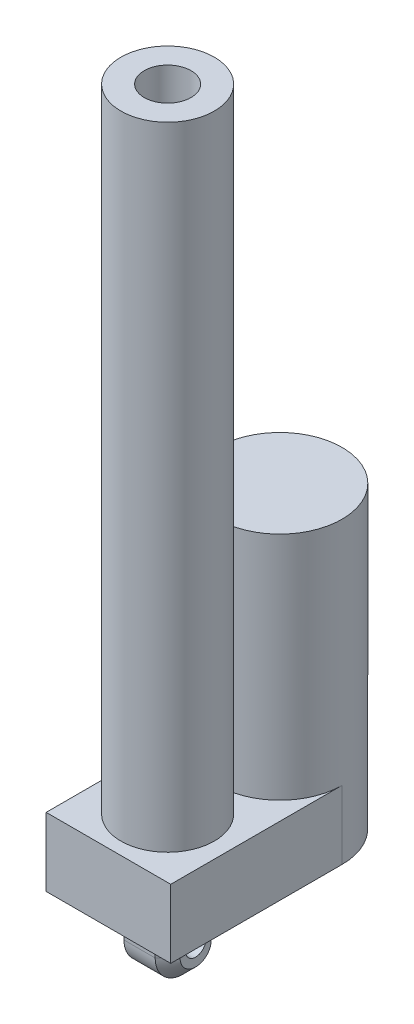
SolidWorks part; units mm, degrees
ref_plane "前视基准面" through (0, 0, 0) normal (0, 0, 1) x (1, 0, 0)
ref_plane "上视基准面" through (0, 0, 0) normal (0, 1, 0) x (1, 0, 0)
ref_plane "右视基准面" through (0, 0, 0) normal (1, 0, 0) x (0, 0, -1)
sketch "草图1" plane through (0, 0, 0) normal (0, 1, 0) x (1, 0, 0)
  line L1 (-20, -27.5) -> (20, -27.5)
  line L2 (-20, -27.5) -> (-20, 27.5)
  line L4 (20, -27.5) -> (20, 27.5)
  line L5 (-20, -27.5) -> (20, 27.5) construction
  line L6 (-20, 27.5) -> (20, -27.5) construction
  arc A0 (20, 27.5) -> (-20, 27.5) centre (0, 27.5) ccw
  point P0 (0, 0)
  dimension "D2" = 55
  dimension "D1" = 40
extrude "凸台-拉伸1" add sketch "草图1" along normal blind 22
sketch "草图2" plane through (0, 22, 0) normal (0, 1, 0) x (1, 0, 0)
  circle A0 centre (0, 27.5) radius 20
  dimension "D2" = 40
extrude "凸台-拉伸2" add sketch "草图2" along normal blind 74
sketch "草图3" plane through (0, 22, 0) normal (0, 1, 0) x (1, 0, 0)
  circle A0 centre (0, -8.5) radius 15
  dimension "D2" = 30
  dimension "D1" = 19
extrude "凸台-拉伸3" add sketch "草图3" along normal blind 203
sketch "草图4" plane through (0, 225, 0) normal (0, 1, 0) x (1, 0, 0)
  circle A0 centre (0, -8.5) radius 7.5
  dimension "D1" = 15
extrude "切除-拉伸1" cut sketch "草图4" against normal blind 150
sketch "草图5" plane through (0, 0, 0) normal (0, -1, 0) x (1, 0, 0)
  line L0 (-20, 27.5) -> (20, 27.5) construction
  line L1 (-9, -0.5) -> (9, -0.5)
  line L2 (-9, -0.5) -> (-9, 17.5)
  line L3 (-9, 17.5) -> (9, 17.5)
  line L4 (9, -0.5) -> (9, 17.5)
  line L5 (-9, -0.5) -> (9, 17.5) construction
  line L6 (-9, 17.5) -> (9, -0.5) construction
  point P0 (0, 8.5)
  dimension "D1" = 19
  dimension "D2" = 18
  dimension "D3" = 18
extrude "凸台-拉伸4" add sketch "草图5" along normal blind 20
sketch "草图6" plane through (-9, 0, 0) normal (-1, 0, 0) x (0, 0, 1)
  line L1 (8.5, -20) -> (-0.5, -20)
  line L4 (-0.5, -20) -> (-0.5, -11)
  arc A0 (-0.5, -11) -> (8.5, -20) centre (8.5, -11) ccw
  dimension "D2" = 18
  dimension "D1" = 11
extrude "切除-拉伸2" cut sketch "草图6" against normal through all both and the other way through all
sketch "草图7" plane through (-9, 0, 0) normal (-1, 0, 0) x (0, 0, 1)
  line L0 (8.5, -20) -> (17.5, -20)
  line L1 (17.5, -20) -> (17.5, -11)
  arc A0 (8.5, -20) -> (17.5, -11) centre (8.5, -11) ccw
extrude "切除-拉伸3" cut sketch "草图7" against normal through all both and the other way through all
chamfer "倒角1" distance 4 angle 45 3 edges at (-9, -5.5, -0.5) (-9, -20, 8.5) (-9, -5.5, 17.5)
chamfer "倒角2" distance 4 angle 45 3 edges at (9, -5.5, -0.5) (9, -20, 8.5) (9, -5.5, 17.5)
sketch "草图8" plane through (9, 0, 0) normal (1, 0, 0) x (0, 0, -1)
  circle A0 centre (-8.5, -10) radius 3.25
  dimension "D1" = 6.5
  dimension "D2" = 10
extrude "切除-拉伸4" cut sketch "草图8" against normal through all both and the other way through all
